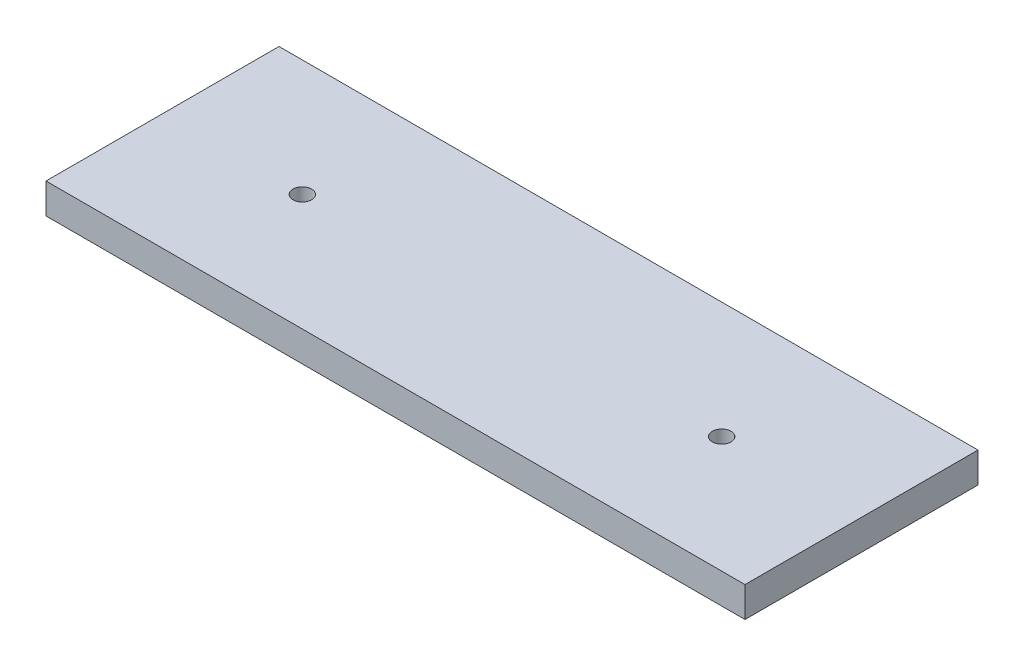
SolidWorks part; units mm, degrees
ref_plane "Front Plane" through (0, 0, 0) normal (0, 0, 1) x (1, 0, 0)
ref_plane "Top Plane" through (0, 0, 0) normal (0, 1, 0) x (1, 0, 0)
ref_plane "Right Plane" through (0, 0, 0) normal (1, 0, 0) x (0, 0, -1)
sketch "Sketch1" plane through (0, 0, 0) normal (0, 1, 0) x (1, 0, 0)
  line L1 (-75, 25) -> (75, 25)
  line L2 (-75, 25) -> (-75, -25)
  line L3 (-75, -25) -> (75, -25)
  line L4 (75, 25) -> (75, -25)
  line L5 (-75, 25) -> (75, -25) construction
  line L6 (-75, -25) -> (75, 25) construction
  point P0 (0, 0)
  dimension "D1" = 50
  dimension "D2" = 150
extrude "Boss-Extrude1" add sketch "Sketch1" along normal blind 6.5
sketch "Sketch3" plane through (0, 0, 0) normal (0, -1, 0) x (1, 0, 0)
  line L0 (75, 0) -> (-75, 0) construction
  line L1 (75, 25) -> (75, -25) construction
  line L2 (-75, -25) -> (-75, 25) construction
  circle A0 centre (45, 0) radius 5
  circle A1 centre (-45, 0) radius 5
  dimension "D1" = 30
  dimension "D2" = 30
extrude "Boss-Extrude2" add sketch "Sketch3" along normal blind 17.5
fillet "Fillet1" radius 5 2 edges at (-45, 0, 5) (45, 0, 5)
sketch "Sketch4" plane through (0, -17.5, 0) normal (0, -1, 0) x (1, 0, 0)
  circle A0 centre (45, 0) radius 3.2
  circle A1 centre (-45, 0) radius 3.2
extrude "Cut-Extrude1" cut sketch "Sketch4" against normal blind 17.5
sketch "Sketch5" plane through (0, 0, 0) normal (0, -1, 0) x (1, 0, 0)
  circle A0 centre (45, 0) radius 2
  circle A1 centre (-45, 0) radius 2
extrude "Cut-Extrude2" cut sketch "Sketch5" against normal blind 6.5
